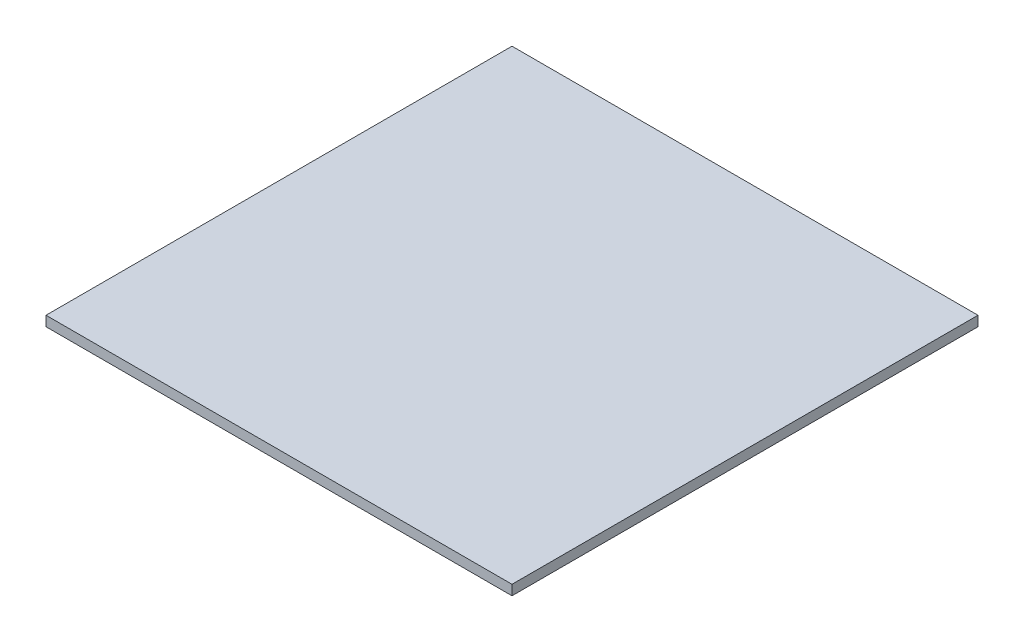
SolidWorks part; units mm, degrees
ref_plane "Front Plane" through (0, 0, 0) normal (0, 0, 1) x (1, 0, 0)
ref_plane "Top Plane" through (0, 0, 0) normal (0, 1, 0) x (1, 0, 0)
ref_plane "Right Plane" through (0, 0, 0) normal (1, 0, 0) x (0, 0, -1)
sketch "Sketch1" plane through (0, 0, 0) normal (0, 1, 0) x (1, 0, 0)
  line L5 (0, 0) -> (280, 0)
  line L6 (0, 0) -> (0, 280)
  line L7 (0, 280) -> (280, 280)
  line L8 (280, 0) -> (280, 280)
  dimension "D1" = 280
  dimension "D2" = 280
extrude "Boss-Extrude1" add sketch "Sketch1" along normal blind 6 contours L7 L8 L5 L6
